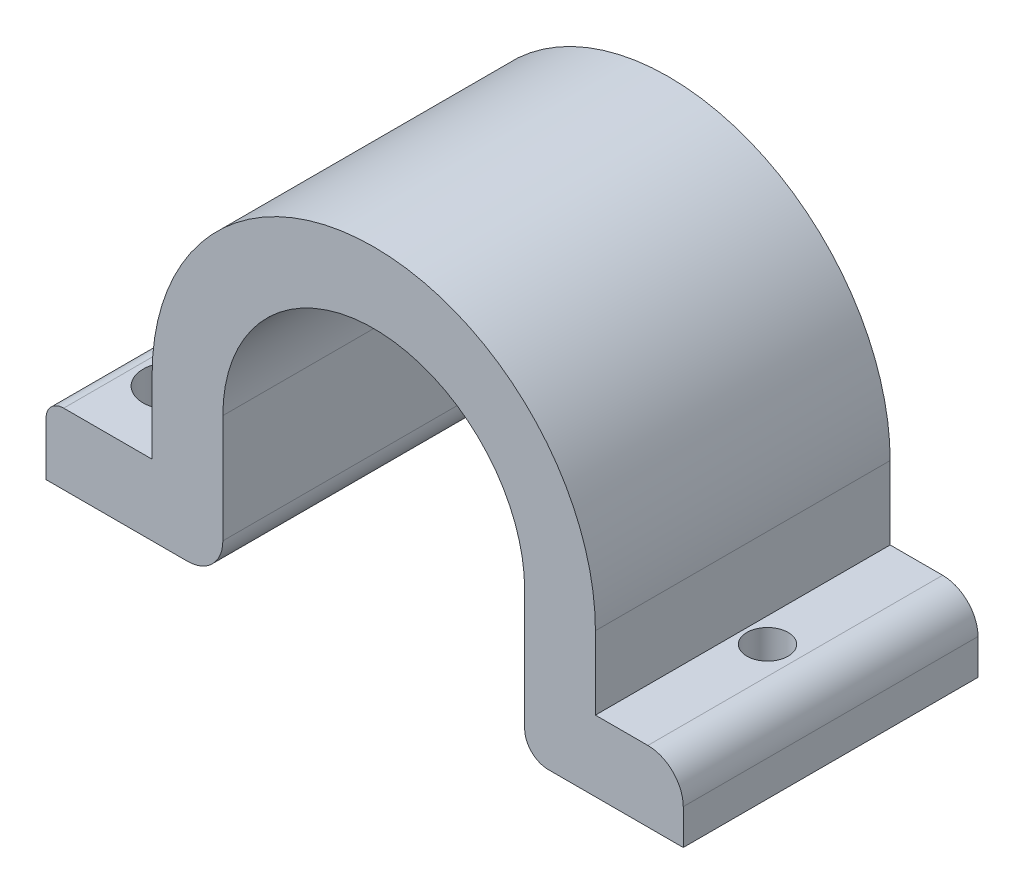
SolidWorks part; units mm, degrees
ref_plane "Front Plane" through (0, 0, 0) normal (0, 0, 1) x (1, 0, 0)
ref_plane "Top Plane" through (0, 0, 0) normal (0, 1, 0) x (1, 0, 0)
ref_plane "Right Plane" through (0, 0, 0) normal (1, 0, 0) x (0, 0, -1)
sketch "Esquisse1" plane through (0, 0, 0) normal (0, 0, 1) x (1, 0, 0)
  line L0 (0.3971, 57.0767) -> (10.3971, 57.0767)
  line L1 (13.3971, 60.0767) -> (13.3971, 69.2767)
  line L2 (38.9971, 69.2767) -> (38.9971, 59.0767)
  line L3 (40.9971, 57.0767) -> (49.4206, 57.0767)
  line L4 (0.3971, 63.0767) -> (7.3971, 63.0767)
  line L5 (7.3971, 63.0767) -> (7.3971, 69.2767)
  line L6 (44.9971, 69.2767) -> (44.9971, 63.0767)
  line L7 (44.9971, 63.0767) -> (49.4206, 63.0767)
  line L8 (-1.6029, 57.0767) -> (-1.6029, 63.0767)
  line L9 (49.4206, 57.0767) -> (52.4473, 57.0767)
  line L10 (52.4473, 57.0767) -> (52.4473, 63.0767)
  line L11 (52.4473, 63.0767) -> (49.4206, 63.0767)
  line L12 (0.3971, 63.0767) -> (-1.6029, 63.0767)
  line L13 (0.3971, 57.0767) -> (-1.6029, 57.0767)
  arc A0 (10.3971, 57.0767) -> (13.3971, 60.0767) centre (10.3971, 60.0767) ccw
  arc A1 (13.3971, 69.2767) -> (38.9971, 69.2767) centre (26.1971, 69.2767) cw
  arc A2 (38.9971, 59.0767) -> (40.9971, 57.0767) centre (40.9971, 59.0767) ccw
  arc A3 (7.3971, 63.0767) -> (7.3971, 63.0767) centre (7.3971, 63.0767) ccw
  arc A4 (7.3971, 69.2767) -> (44.9971, 69.2767) centre (26.1971, 69.2767) cw
  arc A5 (44.9971, 63.0767) -> (44.9971, 63.0767) centre (44.9971, 63.0767) ccw
  dimension "D2" = 15
  dimension "D1" = 6
extrude "Boss.-Extru.1" add sketch "Esquisse1" along normal mid plane 25
sketch "Esquisse2" plane through (0, 63.0767, 0) normal (0, 1, 0) x (1, 0, 0)
  line L0 (0, 0) -> (52.4473, 0) construction
  line L1 (7.3971, 0) -> (-1.6029, 12.5) construction
  line L2 (7.3971, -12.5) -> (7.3971, 12.5) construction
  line L5 (52.4473, -12.5) -> (52.4473, 12.5) construction
  circle A0 centre (2.8971, 6.25) radius 2.5
  circle A4 centre (2.8971, -6.25) radius 2.5
  circle A5 centre (47.0934, 0) radius 1.75
  point P15 (47.424, 0)
  point P16 (2.8971, 6.25)
  point P17 (0, 0)
  point P18 (47.0934, 0)
  dimension "D1" = 5
  dimension "D2" = 3.5
extrude "Enlèv. mat.-Extru.1" cut sketch "Esquisse2" against normal blind 10 contours A0 | A4 | A5
fillet "Congé4" radius 3 1 edges at (52.4473, 63.0767, 0)
fillet "Congé5" radius 1.5 1 edges at (-1.6029, 63.0767, 0)
